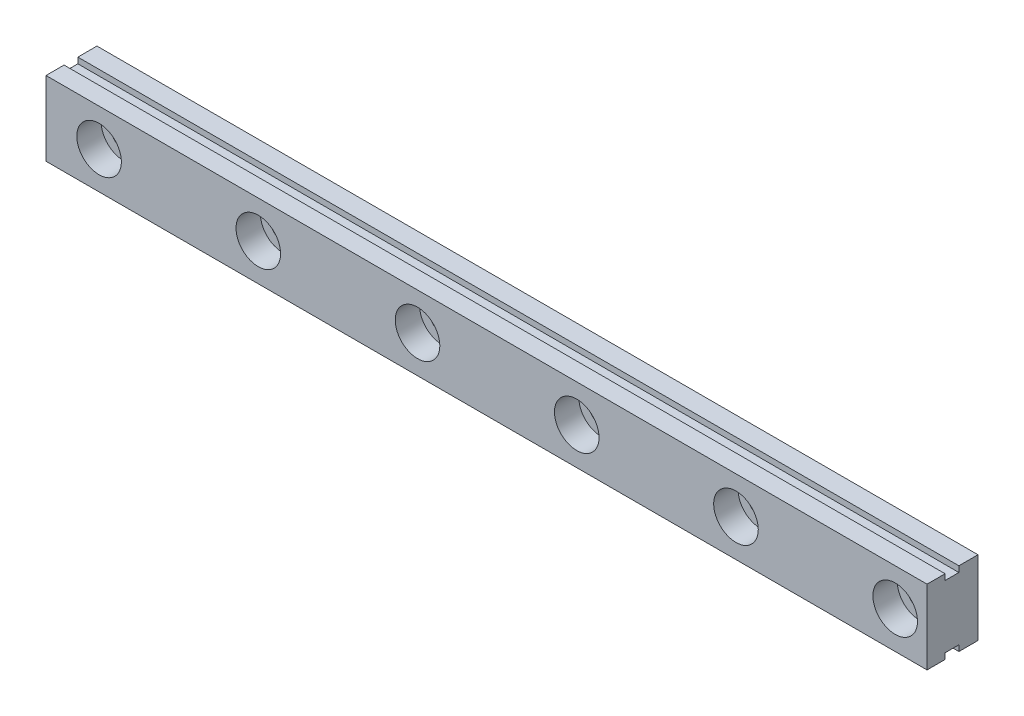
SolidWorks part; units mm, degrees
ref_plane "前视基准面" through (0, 0, 0) normal (0, 0, 1) x (1, 0, 0)
ref_plane "上视基准面" through (0, 0, 0) normal (0, 1, 0) x (1, 0, 0)
ref_plane "右视基准面" through (0, 0, 0) normal (1, 0, 0) x (0, 0, -1)
other "Configuration Table"
sketch "100 mm MGN7 rail 7 x 4.8 mm profile" plane through (0, 0, 0) normal (0, 0, 1) x (1, 0, 0)
  line L0 (-17, 15.5) -> (83, 15.5)
  line L1 (83, 15.5) -> (83, 22.5)
  line L2 (83, 22.5) -> (-17, 22.5)
  line L3 (-17, 22.5) -> (-17, 15.5)
extrude "100 mm MGN7 rail 7 x 4.8 mm" add sketch "100 mm MGN7 rail 7 x 4.8 mm profile" along normal blind 4.8 from offset 32.4
sketch "Nominal raceway clearance profile" plane through (0, 0, 0) normal (0, 0, 1) x (1, 0, 0)
  line L0 (-17.1, 15) -> (83.1, 15)
  line L1 (83.1, 15) -> (83.1, 16.05)
  line L2 (83.1, 16.05) -> (-17.1, 16.05)
  line L3 (-17.1, 16.05) -> (-17.1, 15)
  line L4 (-17.1, 21.95) -> (83.1, 21.95)
  line L5 (83.1, 21.95) -> (83.1, 23)
  line L6 (83.1, 23) -> (-17.1, 23)
  line L7 (-17.1, 23) -> (-17.1, 21.95)
extrude "Nominal raceway clearance" cut sketch "Nominal raceway clearance profile" along normal blind 1.3 from offset 34.2
sketch "Seven rail mounting holes 15 mm pitch profile" plane through (0, 0, 0) normal (0, 0, 1) x (1, 0, 0)
  circle A0 centre (-12, 19) radius 1.2
  circle A1 centre (3, 19) radius 1.2
  circle A2 centre (18, 19) radius 1.2
  circle A3 centre (33, 19) radius 1.2
  circle A4 centre (48, 19) radius 1.2
  circle A5 centre (63, 19) radius 1.2
  circle A6 centre (78, 19) radius 1.2
  point P14 (-17, 15)
  dimension "D3" = 2.4
  dimension "D6" = 2.4
  dimension "D9" = 2.4
  dimension "D12" = 2.4
  dimension "D15" = 2.4
  dimension "D18" = 2.4
  dimension "D21" = 2.4
  dimension "D1" = 5
  dimension "D2" = 4
  dimension "D4" = 20
  dimension "D5" = 4
  dimension "D7" = 35
  dimension "D8" = 4
  dimension "D10" = 50
  dimension "D11" = 4
  dimension "D13" = 65
  dimension "D14" = 4
  dimension "D16" = 80
  dimension "D17" = 4
  dimension "D19" = 95
  dimension "D20" = 4
extrude "Seven rail mounting holes 15 mm pitch" cut sketch "Seven rail mounting holes 15 mm pitch profile" along normal blind 5 from offset 32.3
sketch "M2 rail bolt counterbores diameter 4.2 profile" plane through (0, 0, 0) normal (0, 0, 1) x (1, 0, 0)
  circle A0 centre (-12, 19) radius 2.1
  circle A1 centre (3, 19) radius 2.1
  circle A2 centre (18, 19) radius 2.1
  circle A3 centre (33, 19) radius 2.1
  circle A4 centre (48, 19) radius 2.1
  circle A5 centre (63, 19) radius 2.1
  circle A6 centre (78, 19) radius 2.1
  point P14 (-17, 15)
  dimension "D3" = 4.2
  dimension "D6" = 4.2
  dimension "D9" = 4.2
  dimension "D12" = 4.2
  dimension "D15" = 4.2
  dimension "D18" = 4.2
  dimension "D21" = 4.2
  dimension "D1" = 5
  dimension "D2" = 4
  dimension "D4" = 20
  dimension "D5" = 4
  dimension "D7" = 35
  dimension "D8" = 4
  dimension "D10" = 50
  dimension "D11" = 4
  dimension "D13" = 65
  dimension "D14" = 4
  dimension "D16" = 80
  dimension "D17" = 4
  dimension "D19" = 95
  dimension "D20" = 4
extrude "M2 rail bolt counterbores diameter 4.2" cut sketch "M2 rail bolt counterbores diameter 4.2 profile" along normal blind 2.4 from offset 34.9
sketch "草图1" plane through (0, 0, 37.2) normal (0, 0, 1) x (1, 0, 0)
  line L6 (83, 22.5) -> (66, 22.5)
  line L7 (83, 22.5) -> (83, 15.5)
  line L8 (83, 15.5) -> (66, 15.5)
  line L9 (66, 22.5) -> (66, 15.5)
  circle A1 centre (48, 19) radius 2.1 construction
  dimension "D2" = 18
extrude "切除-拉伸1" cut sketch "草图1" against normal blind 10
